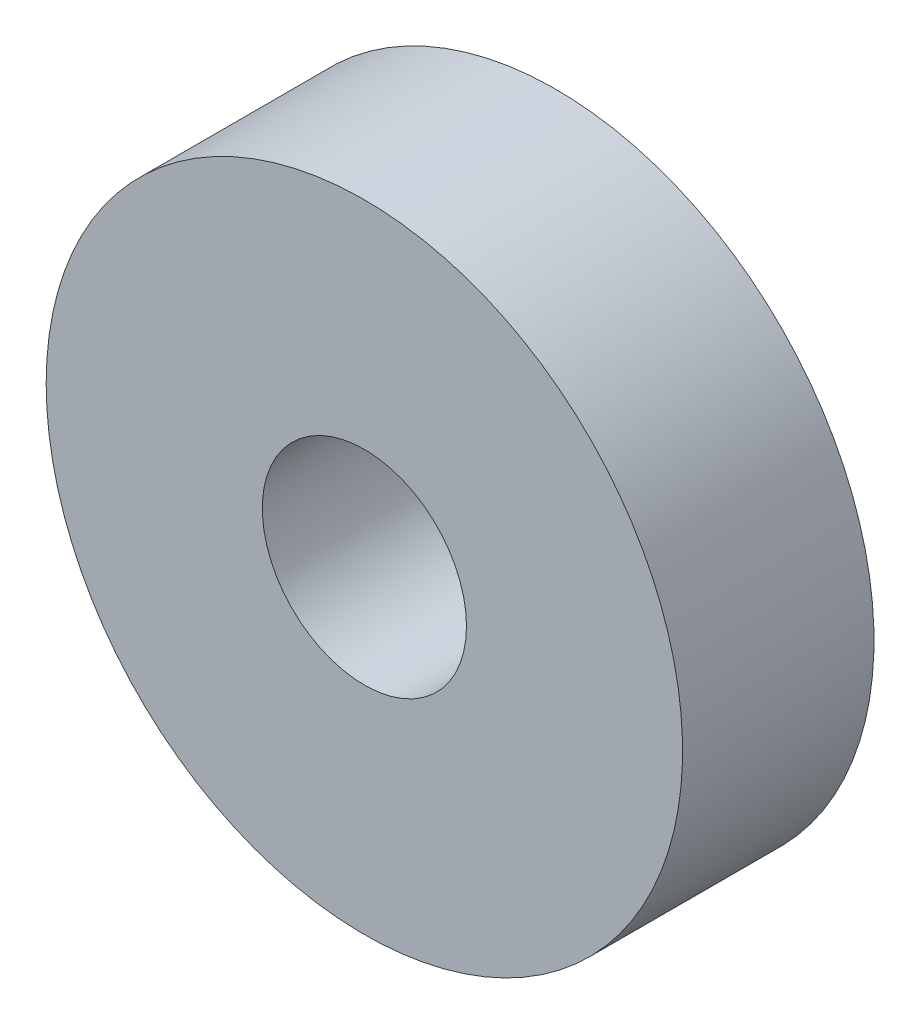
SolidWorks part; units mm, degrees
ref_plane "前视基准面" through (0, 0, 0) normal (0, 0, 1) x (1, 0, 0)
ref_plane "上视基准面" through (0, 0, 0) normal (0, 1, 0) x (1, 0, 0)
ref_plane "右视基准面" through (0, 0, 0) normal (1, 0, 0) x (0, 0, -1)
ref_plane "基准面4" through (0, 0, 0) normal (0, -1, 0) x (1, 0, 0)
sketch "草图1" plane through (0, 0, 0) normal (0, -1, 0) x (1, 0, 0)
  line L0 (4.9872, 3) -> (1.35, 3)
  line L1 (1.35, 3) -> (1.35, 0)
  line L2 (1.35, 0) -> (4.9872, 0)
  line L3 (4.9872, 0) -> (4.9872, 3)
  line L4 (0, 3) -> (0, 0) construction
revolve "旋转1" add sketch "草图1" angle 360 about L4
sketch "草图2" plane through (0, 0, 3) normal (0, 0, 1) x (1, 0, 0)
  circle A0 centre (0, 0) radius 1.6
  dimension "D1" = 3.2
extrude "切除-拉伸1" cut sketch "草图2" against normal through all
